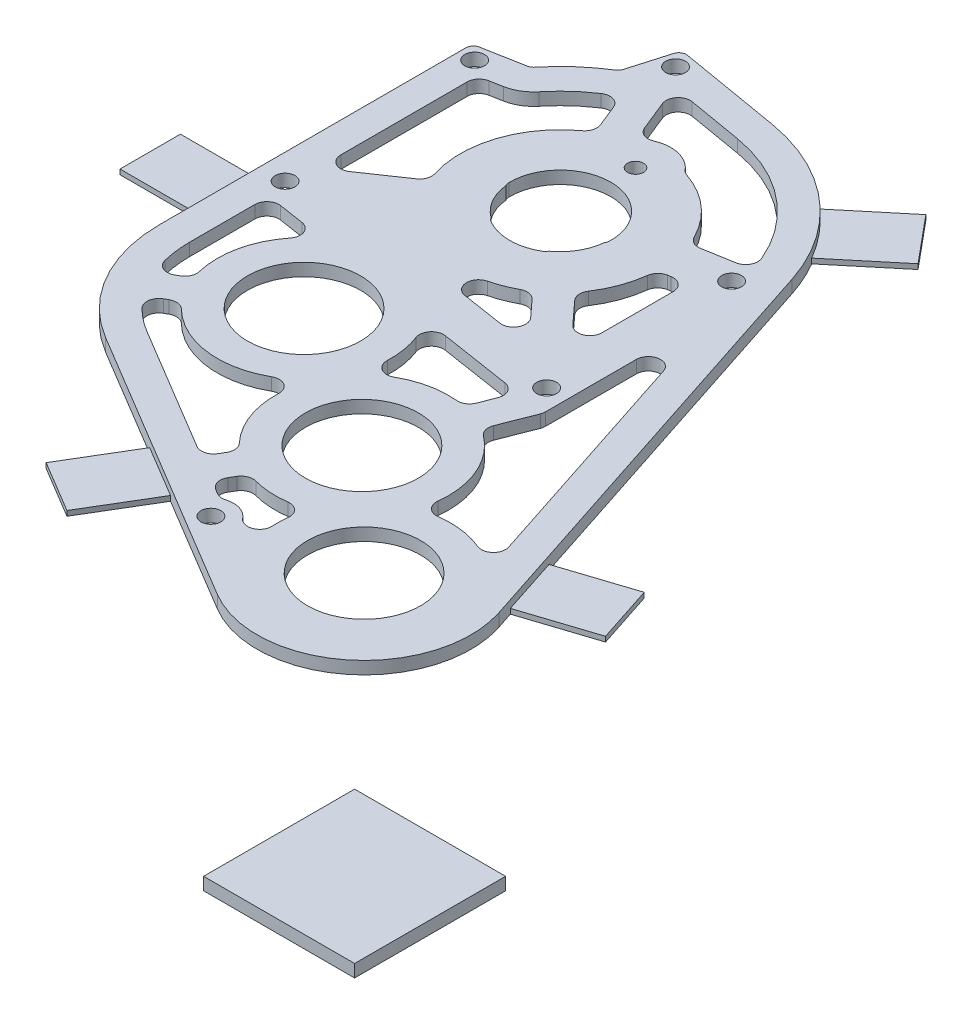
SolidWorks part; units mm, degrees
material "6061-T6 (SS)"
ref_plane "Front Plane" through (0, 0, 0) normal (0, 0, 1) x (1, 0, 0)
ref_plane "Top Plane" through (0, 0, 0) normal (0, 1, 0) x (1, 0, 0)
ref_plane "Right Plane" through (0, 0, 0) normal (1, 0, 0) x (0, 0, -1)
sketch "Underlying Sketch" plane through (0, 0, 0) normal (0, 1, 0) x (1, 0, 0)
  line L0 (316.166, 172.527) -> (324.7595, 250.8659) construction
  line L1 (305.0323, 171.3482) -> (280.2246, 246.1507) construction
  line L2 (305.0323, 171.3482) -> (280.2246, 246.1507)
  line L3 (324.7595, 250.8659) -> (316.166, 172.527)
  line L4 (352.425, 12.5969) -> (352.425, 407.9875) construction
  line L5 (352.425, 407.9875) -> (-352.425, 407.9875) construction
  line L6 (0, 407.9875) -> (0, 0) construction
  line L7 (200.025, 407.9875) -> (200.025, 255.5875) construction
  line L8 (200.025, 255.5875) -> (-200.025, 255.5875) construction
  line L9 (-200.025, 255.5875) -> (-200.025, 407.9875) construction
  line L10 (200.025, 204.7875) -> (-16.5927, 204.7875) construction
  line L11 (293.9415, 393.446) -> (335.8515, 393.446) construction
  line L12 (293.9415, 393.446) -> (293.9415, 266.446) construction
  line L13 (293.9415, 266.446) -> (335.8515, 266.446) construction
  line L14 (335.8515, 393.446) -> (335.8515, 266.446) construction
  line L15 (293.9415, 393.446) -> (335.8515, 266.446) construction
  line L16 (293.9415, 266.446) -> (335.8515, 393.446) construction
  line L17 (212.725, 407.9875) -> (212.725, 36.8617) construction
  line L18 (240.284, 194.6275) -> (324.866, 194.6275) construction
  line L19 (227.584, 181.9275) -> (227.584, 143.0655) construction
  line L20 (240.284, 130.3655) -> (324.866, 130.3655) construction
  line L21 (337.566, 181.9275) -> (337.566, 143.0655) construction
  line L22 (227.584, 143.0655) -> (212.725, 143.0655) construction
  line L23 (337.566, 143.0655) -> (352.425, 143.0655) construction
  line L24 (204.4319, 357.1875) -> (204.4319, 303.637) construction
  line L25 (240.284, 246.0625) -> (324.866, 246.0625) construction
  line L26 (227.584, 258.7625) -> (227.584, 362.6012) construction
  line L28 (337.566, 258.7625) -> (337.566, 376.6884) construction
  line L29 (314.8965, 329.946) -> (257.9415, 329.946) construction
  line L30 (257.9415, 329.946) -> (257.9415, 166.2104) construction
  line L31 (241.4315, 329.946) -> (241.4315, 166.1449) construction
  line L32 (209.55, 387.1595) -> (289.306, 387.1595) construction
  line L33 (289.306, 387.1595) -> (289.306, 273.812) construction
  line L34 (200.025, 348.1437) -> (200.025, 303.637)
  line L35 (217.8019, 272.2835) -> (310.6596, 216.7201)
  circle A0 centre (310.4706, 173.1518) radius 20.2057
  circle A1 centre (310.4706, 173.1518) radius 5.7296 construction
  circle A2 centre (301.9779, 253.365) radius 22.9183 construction
  circle A3 centre (301.9779, 253.365) radius 11.4681
  circle A7 centre (247.65, 357.1875) radius 43.2181
  circle A10 centre (236.5629, 303.637) radius 11.4681
  circle A11 centre (236.5629, 303.637) radius 32.131
  arc A12 (280.2246, 246.1507) -> (324.7595, 250.8659) centre (301.9779, 253.365) cw
  arc A13 (316.166, 172.527) -> (305.0323, 171.3482) centre (310.4706, 173.1518) cw
  circle A14 centre (273.8165, 280.9864) radius 27.9781
  circle A15 centre (273.8165, 280.9864) radius 11.4681
  circle A16 centre (247.65, 357.1875) radius 12.5 construction
  arc A19 (227.584, 143.0655) -> (240.284, 130.3655) centre (240.284, 143.0655) ccw construction
  arc A20 (324.866, 130.3655) -> (337.566, 143.0655) centre (324.866, 143.0655) ccw construction
  arc A21 (324.866, 194.6275) -> (337.566, 181.9275) centre (324.866, 181.9275) cw construction
  arc A22 (240.284, 194.6275) -> (227.584, 181.9275) centre (240.284, 181.9275) ccw construction
  circle A23 centre (247.65, 357.1875) radius 6.35 construction
  arc A24 (324.866, 246.0625) -> (337.566, 258.7625) centre (324.866, 258.7625) ccw construction
  arc A25 (240.284, 246.0625) -> (227.584, 258.7625) centre (240.284, 258.7625) cw construction
  circle A26 centre (301.9779, 253.365) radius 4.7625 construction
  circle A27 centre (273.8165, 280.9864) radius 4.7625 construction
  circle A28 centre (213.0081, 396.113) radius 8.89 construction
  circle A29 centre (213.0081, 396.113) radius 11.2395 construction
  circle A30 centre (213.0081, 396.113) radius 10.16
  circle A31 centre (273.8165, 280.9864) radius 29.21 construction
  circle A32 centre (273.8165, 280.9864) radius 10.2616 construction
  circle A33 centre (284.5435, 363.5375) radius 4.7625 construction
  arc A34 (209.55, 387.1595) -> (200.025, 348.1437) centre (247.65, 357.1875) ccw construction
  circle A35 centre (211.9378, 382.397) radius 4.7625 construction
  circle A36 centre (206.375, 329.037) radius 4.7625 construction
  circle A37 centre (284.5435, 316.865) radius 4.7625 construction
  arc A38 (200.025, 303.637) -> (217.8019, 272.2835) centre (236.5629, 303.637) ccw
  circle A39 centre (301.9779, 253.365) radius 26.9875 construction
  circle A40 centre (270.2279, 246.4633) radius 4.7625 construction
  circle A41 centre (276.098, 369.8875) radius 2.413 construction
  circle A42 centre (225.213, 369.8875) radius 2.4993 construction
  circle A43 centre (309.5625, 204.1525) radius 5.3299 construction
  circle A44 centre (284.734, 230.1875) radius 5.3299 construction
  circle A45 centre (276.098, 382.5748) radius 4.5847 construction
  circle A46 centre (250.656, 382.5748) radius 4.5847 construction
  circle A47 centre (316.5575, 253.365) radius 2.0193 construction
  circle A48 centre (287.3983, 253.365) radius 2.0193 construction
  circle A49 centre (301.9779, 253.365) radius 12.5603 construction
  point P27 (0, 407.9875)
  point P31 (0, 255.5875)
  point P44 (314.8965, 329.946)
  dimension "D1" = 11.4592
  dimension "D2" = 45.8366
  dimension "D3" = 40.4114
  dimension "D4" = 22.9362
  dimension "D5" = 86.4362
  dimension "D6" = 64.262
  dimension "D11" = 55.9562
  dimension "D7" = 25
  dimension "D24" = 12.7
  dimension "D26" = 12.7
  dimension "D29" = 9.525
  dimension "D34" = 17.78
  dimension "D35" = 22.479
  dimension "D36" = 20.32
  dimension "D37" = 58.42
  dimension "D39" = 20.5232
  dimension "D47" = 53.975
  dimension "D61" = 9.1694
  dimension "D62" = 25.1206
  dimension "D63" = 4.0386
  dimension "D64" = 9.525
  dimension "D12" = 704.85
  dimension "D15" = 400.05
  dimension "D13" = 152.4
  dimension "D16" = 47.625
  dimension "D14" = 407.9875
  dimension "D17" = 50.8
  dimension "D18" = 329.946
  dimension "D19" = 127
  dimension "D20" = 41.91
  dimension "D22" = 50.8
  dimension "D23" = 213.36
  dimension "D9" = 14.859
  dimension "D25" = 425.45
  dimension "D27" = 64.262
  dimension "D28" = 51.435
  dimension "D31" = 16.51
  dimension "D32" = 36
  dimension "D33" = 15.875
  dimension "D21" = 293.9415
  dimension "D38" = 0.635
  dimension "D30" = 2.54
  dimension "D10" = 1.27
  dimension "D40" = 20.828
  dimension "D41" = 79.756
  dimension "D42" = 4.6355
  dimension "D43" = 113.3475
  dimension "D45" = 25.4
  dimension "D46" = 63.5
  dimension "D48" = 31.75
  dimension "D50" = 38.1
  dimension "D49" = 17.8435
  dimension "D52" = 25.188
  dimension "D51" = 17.272
  dimension "D53" = 9.525
  dimension "D54" = 42.8625
  dimension "D55" = 15.875
  dimension "D56" = 52.832
  dimension "D57" = 6.35
  dimension "D58" = 6.35
  dimension "D60" = 25.442
  dimension "D59" = 50.631
sketch "Sketch2" plane through (0, 0, 0) normal (0, 1, 0) x (1, 0, 0)
  line L0 (298.0401, 171.8357) -> (322.9011, 174.4679) construction
  line L15 (328.9606, 253.8709) -> (330.4671, 173.5267)
  line L17 (352.425, 407.9875) -> (-352.425, 407.9875) construction
  line L18 (200.025, 348.1437) -> (200.025, 303.637)
  line L21 (310.4706, 173.1518) -> (301.9779, 253.365) construction
  line L22 (200.025, 407.9875) -> (200.025, 255.5875) construction
  line L25 (239.5488, 387.6675) -> (289.306, 387.6675)
  line L27 (289.306, 272.415) -> (289.306, 387.6675)
  line L28 (266.1096, 243.3776) -> (291.4873, 166.8561)
  line L29 (321.0939, 272.415) -> (289.306, 272.415)
  line L30 (305.0323, 171.3482) -> (280.2246, 246.1507) construction
  line L31 (217.8019, 272.2835) -> (266.1096, 243.3776)
  line L32 (284.226, 301.3388) -> (263.407, 260.6339) construction
  circle A0 centre (273.8165, 280.9864) radius 11.1125 construction
  circle A1 centre (236.5629, 303.637) radius 11.1125 construction
  circle A3 centre (310.4706, 173.1518) radius 12.5 construction
  circle A4 centre (322.9011, 174.4679) radius 1.7948 construction
  circle A5 centre (298.0401, 171.8357) radius 1.7948 construction
  arc A8 (330.4671, 173.5267) -> (291.4873, 166.8561) centre (310.4706, 173.1518) cw
  circle A15 centre (310.4706, 173.1518) radius 7.9375
  circle A22 centre (301.9779, 253.365) radius 11.1125 construction
  arc A35 (321.0939, 272.415) -> (328.9606, 253.8709) centre (301.9779, 253.365) cw
  circle A37 centre (285.3372, 316.865) radius 3.9688 construction
  circle A39 centre (301.9779, 253.365) radius 25.4 construction
  circle A40 centre (236.5629, 303.637) radius 33.02 construction
  circle A45 centre (270.2279, 245.5383) radius 3.9688 construction
  circle A46 centre (273.8165, 280.9864) radius 29.21 construction
  arc A47 (279.6365, 268.504) -> (321.0939, 272.415) centre (301.9779, 253.365) ccw construction
  arc A48 (200.025, 303.637) -> (217.8019, 272.2835) centre (236.5629, 303.637) ccw
  circle A49 centre (203.9938, 329.037) radius 3.9688 construction
  arc A50 (239.5488, 387.6675) -> (200.025, 348.1437) centre (239.5488, 348.1437) ccw
  circle A51 centre (247.65, 357.1875) radius 5.08
  circle A54 centre (301.9779, 253.365) radius 11.0934
  circle A55 centre (273.8165, 280.9864) radius 11.0934
  circle A56 centre (236.5629, 303.637) radius 11.0935
  point P46 (284.226, 301.3388)
  point P49 (273.8165, 280.9864)
  point P64 (263.407, 260.6339)
  dimension "D1" = 22.225
  dimension "D2" = 25
  dimension "D4" = 3.5896
  dimension "D5" = 20
  dimension "D7" = 15.875
  dimension "D8" = 26.9875
  dimension "D6" = 7.9375
  dimension "D13" = 50.8
  dimension "D14" = 66.04
  dimension "D17" = 58.42
  dimension "D11" = 10.16
  dimension "D10" = 89.281
  dimension "D3" = 20.32
  dimension "D15" = 63.5
  dimension "D18" = 31.75
  dimension "D19" = 19.05
  dimension "D9" = 25.4
  dimension "D12" = 45.72
  dimension "D16" = 5.08
  dimension "D20" = 0.019
extrude "Boss-Extrude1" [suppressed] add sketch "Sketch2" along normal blind 3.175
hole_wizard "M4 Clearance Hole1" [suppressed] positions "Sketch3" profile "Sketch4" hole size "M4" standard "ANSI Metric"
sketch "Sketch3" [suppressed] plane through (0, 3.175, 0) normal (0, 1, 0) x (1, 0, 0)
  point P0 (322.9011, 174.4679)
  point P2 (298.0401, 171.8357)
sketch "Sketch4" plane through (322.9011, 3.175, -174.4679) normal (1, 0, 0) x (0, 0, 1)
  line L0 (0, 0) -> (0, 3.175)
  line L1 (0, 3.175) -> (2.15, 3.175)
  line L2 (2.15, 3.175) -> (2.15, 0)
  line L5 (2.15, 0) -> (0, 0)
  line L11 (0, -6.35) -> (0, 107.95) construction
  dimension "Thru Hole Dia." = 4.3
  dimension "Thru Hole Depth" = 3.175
hole_wizard "CSK for #8 Flat Head Socket Cap Screw1" [suppressed] positions "Sketch5" profile "Sketch7" countersink size "#8" standard "ANSI Inch"
sketch "Sketch5" [suppressed] plane through (0, 0, 0) normal (0, -1, 0) x (-1, 0, 0)
  line L2 (-254, 357.1875) -> (-260.15, 357.1875) construction
  line L4 (-247.65, 350.8375) -> (-247.65, 344.6875) construction
  line L6 (-241.3, 357.1875) -> (-235.15, 357.1875) construction
  line L8 (-247.65, 363.5375) -> (-247.65, 369.6875) construction
  circle A0 centre (-247.65, 357.1875) radius 6.35 construction
  circle A1 centre (-247.65, 357.1875) radius 12.5 construction
  point P23 (-238.225, 357.1875)
  point P25 (-247.65, 347.7625)
  point P27 (-257.075, 357.1875)
  point P29 (-247.65, 366.6125)
sketch "Sketch7" plane through (247.65, 0, -366.6125) normal (1, 0, 0) x (0, 0, -1)
  line L0 (0, 0) -> (0, 3.175)
  line L1 (0, 3.175) -> (2.1526, 3.175)
  line L2 (2.1526, 3.175) -> (2.1526, 3.0225)
  line L3 (2.1526, 3.0225) -> (4.7801, 0)
  line L5 (4.7801, 0) -> (0, 0)
  line L6 (-2.1526, 3.0225) -> (-4.7801, 0) construction
  line L11 (0, -6.35) -> (0, 107.95) construction
  dimension "Thru Hole Dia." = 4.3053
  dimension "Thru Hole Depth" = 4.7625
  dimension "Near C'Sink Dia." = 9.5602
  dimension "Near C'Sink Angle" = 82
sketch "Sketch8" [suppressed] plane through (0, 0, 0) normal (0, -1, 0) x (1, 0, 0)
  line L0 (254.3145, -350.523) -> (247.65, -357.1875) construction
  line L1 (247.65, -357.1875) -> (260.15, -357.1875) construction
  line L2 (238.8112, -348.3487) -> (243.1599, -352.6974) construction
  circle A1 centre (247.65, -357.1875) radius 12.5 construction
  circle A2 centre (254.3145, -350.523) radius 2.1908
  circle A3 centre (254.3145, -363.852) radius 2.1908
  circle A4 centre (240.9855, -363.852) radius 2.1908
  circle A5 centre (240.9855, -350.523) radius 2.1908
  circle A6 centre (247.65, -357.1875) radius 9.425 construction
  circle A7 centre (247.65, -357.1875) radius 6.35 construction
  point P11 (240.9855, -350.523)
  point P20 (247.65, -357.1875)
  dimension "D2" = 4.3815
  dimension "D4" = 45
  dimension "D3" = 4
extrude "Cut-Extrude1" [suppressed] cut sketch "Sketch8" against normal through all
hole_wizard "#10-32 Tapped Hole1" [suppressed] positions "Sketch9" profile "Sketch10" tap size "#10-32" standard "ANSI Inch"
sketch "Sketch9" [suppressed] plane through (0, 3.175, 0) normal (0, 1, 0) x (1, 0, 0)
  point P0 (270.2279, 246.4633)
  point P3 (284.5435, 316.865)
  point P6 (284.5435, 363.5375)
  point P14 (206.375, 329.037)
  point P19 (276.098, 369.8875)
  point P23 (225.213, 369.8875)
  point P27 (309.5625, 204.1525)
  point P35 (284.734, 230.1875)
  point P41 (284.226, 301.3388)
  point P44 (263.407, 260.6339)
sketch "Sketch10" plane through (270.2279, 3.175, -246.4633) normal (1, 0, 0) x (0, 0, 1)
  line L0 (0, 0) -> (0, 3.175)
  line L1 (0, 3.175) -> (2.0193, 3.175)
  line L2 (2.0193, 3.175) -> (2.0193, 0)
  line L5 (2.0193, 0) -> (0, 0)
  line L11 (0, -6.35) -> (0, 107.95) construction
  dimension "Thru Tap Drill Dia." = 4.0386
  dimension "Thru Tap Drill Depth" = 3.175
cosmetic thread "Hole Thread3" parameters "D2"=4.826
cosmetic thread "Hole Thread5" parameters "D2"=4.826
cosmetic thread "Hole Thread6" [suppressed] parameters "D2"=4.826
cosmetic thread "Hole Thread7" [suppressed] parameters "D2"=4.826
cosmetic thread "Hole Thread9" [suppressed] parameters "D2"=4.826
cosmetic thread "Hole Thread10" [suppressed] parameters "D2"=4.826
cosmetic thread "Hole Thread11" [suppressed] parameters "D2"=4.826
cosmetic thread "Hole Thread14" [suppressed] parameters "D2"=4.826
cosmetic thread "Hole Thread16" [suppressed] parameters "D2"=4.826
cosmetic thread "Hole Thread17" [suppressed] parameters "D2"=4.826
sketch "Sketch12" plane through (0, 0, 0) normal (0, 1, 0) x (1, 0, 0)
  line L0 (200.025, 303.637) -> (200.025, 357.1875)
  line L1 (200.025, 407.9875) -> (200.025, 255.5875) construction
  line L5 (217.8019, 272.2835) -> (288.1207, 230.2068)
  line L11 (291.75, 371.5926) -> (327.6315, 261.7446)
  line L14 (200.025, 382.5838) -> (200.025, 357.1875)
  line L15 (352.425, 407.9875) -> (-352.425, 407.9875) construction
  line L16 (255.4549, 402.9194) -> (227.9505, 407.6134)
  line L17 (227.9505, 407.6134) -> (224.4061, 395.4181)
  line L19 (212.5142, 384.8882) -> (200.025, 382.5838)
  line L20 (230.6604, 403.2859) -> (247.65, 357.1875) construction
  line L21 (243.984, 382.3869) -> (240.318, 376.0372) construction
  line L22 (240.318, 376.0372) -> (243.984, 369.6875) construction
  line L23 (243.984, 369.6875) -> (251.316, 369.6875) construction
  line L24 (251.316, 369.6875) -> (254.982, 376.0372) construction
  line L25 (254.982, 376.0372) -> (251.316, 382.3869) construction
  line L26 (251.316, 382.3869) -> (243.984, 382.3869) construction
  line L27 (247.65, 357.1875) -> (203.835, 379.4125) construction
  line L28 (230.6604, 403.2859) -> (213.0081, 396.113) construction
  line L29 (213.0081, 396.113) -> (203.835, 379.4125) construction
  arc A3 (327.6315, 261.7446) -> (288.1207, 230.2068) centre (301.9779, 253.365) cw
  arc A5 (217.8019, 272.2835) -> (200.025, 303.637) centre (236.5629, 303.637) cw
  circle A8 centre (236.5629, 303.637) radius 14.2875 construction
  circle A9 centre (273.8165, 280.9864) radius 14.2875 construction
  circle A10 centre (301.9779, 253.365) radius 14.2875 construction
  circle A15 centre (213.0081, 396.113) radius 3.9687 construction
  arc A16 (255.4549, 402.9194) -> (291.75, 371.5926) centre (247.65, 357.1875) cw
  arc A18 (224.4061, 395.4181) -> (212.5142, 384.8882) centre (247.65, 357.1875) ccw
  circle A19 centre (247.65, 357.1875) radius 12.5 construction
  circle A20 centre (247.65, 376.0372) radius 5.1722 construction
  circle A21 centre (247.65, 376.1896) radius 2.0193 construction
  circle A22 centre (247.65, 357.1875) radius 43.2181 construction
  circle A23 centre (203.835, 379.4125) radius 3.81 construction
  circle A24 centre (230.6604, 403.2859) radius 3.81 construction
  circle A25 centre (273.8165, 280.9864) radius 14.2684
  circle A26 centre (301.9779, 253.365) radius 14.2684
  circle A27 centre (236.5629, 303.637) radius 14.2684
  circle A28 centre (213.0081, 396.113) radius 7.366 construction
  point P63 (247.65, 369.6875)
  dimension "D1" = 26.9875
  dimension "D3" = 28.575
  dimension "D7" = 7.9375
  dimension "D8" = 7.62
  dimension "D11" = 25
  dimension "D14" = 4.0386
  dimension "D9" = 14.732
  dimension "D12" = 7.332
  dimension "D13" = 0.1524
  dimension "D4" = 0.019
  dimension "D2" = 3.175
  dimension "D5" = 28.575
  dimension "D6" = 12.7
extrude "Boss-Extrude2" add sketch "Sketch12" along normal blind 3.175
fillet "Fillet1" [suppressed] radius 5.08
hole_wizard "#10 Clearance Hole1" positions "Sketch13" profile "Sketch14" hole size "#10" standard "ANSI Inch"
sketch "Sketch13" plane through (0, 3.175, 0) normal (0, 1, 0) x (1, 0, 0)
  point P0 (206.375, 329.037)
  point P6 (284.5435, 363.5375)
  point P9 (284.5435, 316.865)
  point P12 (270.2279, 246.4633)
  point P15 (203.835, 379.4125)
  point P18 (230.6604, 403.2859)
sketch "Sketch14" plane through (206.375, 3.175, -329.037) normal (1, 0, 0) x (0, 0, 1)
  line L0 (0, 0) -> (0, 17.3707)
  line L1 (0, 17.3707) -> (2.4892, 15.875)
  line L2 (2.4892, 15.875) -> (2.4892, 0)
  line L5 (2.4892, 0) -> (0, 0)
  line L10 (0, 17.3707) -> (-2.4892, 15.875) construction
  line L11 (0, -6.35) -> (0, 107.95) construction
  dimension "Hole Dia." = 4.9784
  dimension "Hole Depth" = 15.875
  dimension "Drill Angle" = 118
sketch "Sketch16" [suppressed] plane through (0, 0, 0) normal (0, 1, 0) x (1, 0, 0)
  line L18 (201.2282, 396.9698) -> (199.9717, 379.6935)
  line L19 (207.5383, 378.2768) -> (208.8669, 382.6093)
  line L21 (213.5243, 407.9127) -> (230.8297, 407.1557)
  line L22 (231.3586, 399.4758) -> (226.9012, 398.659)
  arc A8 (208.8669, 382.6093) -> (211.5985, 384.3864) centre (211.2953, 381.8646) cw
  arc A9 (224.8191, 396.1521) -> (226.9012, 398.659) centre (227.359, 396.1606) cw
  circle A10 centre (213.0081, 396.113) radius 5.1435
  arc A13 (211.5985, 384.3864) -> (224.8191, 396.1521) centre (213.0081, 396.113) ccw
  arc A15 (199.9717, 379.6935) -> (207.5383, 378.2768) centre (203.835, 379.4125) ccw
  arc A16 (230.8297, 407.1557) -> (231.3586, 399.4758) centre (230.6604, 403.2859) cw
  arc A17 (213.5243, 407.9127) -> (201.2282, 396.9698) centre (213.0081, 396.113) ccw
  dimension "D1" = 11.811
  dimension "D2" = 2.54
  dimension "D3" = 10.287
  dimension "D4" = 7.747
extrude "Boss-Extrude3" [suppressed] add sketch "Sketch16" along normal blind 2.286
hole_wizard "#10-32 Tapped Hole2" [suppressed] positions "Sketch17" profile "Sketch18" tap size "#10-32" standard "ANSI Inch"
sketch "Sketch17" plane through (0, 2.286, 0) normal (0, 1, 0) x (1, 0, 0)
  point P0 (203.835, 379.4125)
  point P3 (230.6604, 403.2859)
sketch "Sketch18" plane through (203.835, 2.286, -379.4125) normal (1, 0, 0) x (0, 0, 1)
  line L0 (0, 0) -> (0, 14.8277)
  line L1 (0, 14.8277) -> (2.0193, 13.6144)
  line L2 (2.0193, 13.6144) -> (2.0193, 0)
  line L5 (2.0193, 0) -> (0, 0)
  line L10 (0, 14.8277) -> (-2.0193, 13.6144) construction
  line L11 (0, -6.35) -> (0, 107.95) construction
  dimension "Tap Drill Dia." = 4.0386
  dimension "Tap Drill Depth" = 13.6144
  dimension "Drill Angle" = 118
cosmetic thread "Hole Thread12" [suppressed] parameters "D1"=2.286, "D2"=4.826
cosmetic thread "Hole Thread13" [suppressed] parameters "D1"=2.286, "D2"=4.826
hole_wizard "#10-32 Tapped Hole3 for fixture clamp" positions "Sketch19" profile "Sketch20" tap size "#10-32" standard "ANSI Inch"
sketch "Sketch19" plane through (0, 3.175, 0) normal (0, 1, 0) x (1, 0, 0)
  point P0 (247.65, 376.1896)
sketch "Sketch20" plane through (247.65, 3.175, -376.1896) normal (1, 0, 0) x (0, 0, 1)
  line L0 (0, 0) -> (0, 14.8277)
  line L1 (0, 14.8277) -> (2.0193, 13.6144)
  line L2 (2.0193, 13.6144) -> (2.0193, 0)
  line L5 (2.0193, 0) -> (0, 0)
  line L10 (0, 14.8277) -> (-2.0193, 13.6144) construction
  line L11 (0, -6.35) -> (0, 107.95) construction
  dimension "Tap Drill Dia." = 4.0386
  dimension "Tap Drill Depth" = 13.6144
  dimension "Drill Angle" = 118
cosmetic thread "Hole Thread15" parameters "D1"=3.175, "D2"=4.826
sketch "Spacer Plate" [suppressed] plane through (0, 0, 0) normal (0, 1, 0) x (1, 0, 0)
  line L5 (240.284, 194.6275) -> (324.866, 194.6275) construction
  arc A1 (293.5407, 226.5588) -> (275.2197, 230.6391) centre (284.734, 230.1875) ccw
  arc A3 (275.2197, 230.6391) -> (309.5625, 194.6275) centre (309.5625, 229.009) ccw
  arc A6 (309.5625, 194.6275) -> (306.3554, 213.1213) centre (309.5625, 204.1525) ccw
  arc A7 (306.3554, 213.1213) -> (293.5407, 226.5588) centre (302.9345, 222.6881) cw
  dimension "D1" = 9.525
  dimension "D2" = 10.16
extrude "Spacer Plate Extrude" [suppressed] add sketch "Spacer Plate" along normal blind 2.286
hole_wizard "#10 Clearance Hole2" [suppressed] positions "Sketch22" profile "Sketch23" hole size "#10" standard "ANSI Inch"
sketch "Sketch22" plane through (0, 2.286, 0) normal (0, 1, 0) x (1, 0, 0)
  point P0 (309.5625, 204.1525)
  point P3 (284.734, 230.1875)
sketch "Sketch23" plane through (309.5625, 2.286, -204.1525) normal (1, 0, 0) x (0, 0, 1)
  line L0 (0, 0) -> (0, 2.286)
  line L1 (0, 2.286) -> (2.4892, 2.286)
  line L2 (2.4892, 2.286) -> (2.4892, 0)
  line L5 (2.4892, 0) -> (0, 0)
  line L11 (0, -6.35) -> (0, 107.95) construction
  dimension "Thru Hole Dia." = 4.9784
  dimension "Thru Hole Depth" = 2.286
sketch "Sketch24" [suppressed] plane through (0, 0, 0) normal (0, 1, 0) x (1, 0, 0)
  line L1 (220.134, 387.1595) -> (246.0967, 387.1595)
  line L2 (257.5267, 376.9995) -> (220.134, 376.9995)
  line L3 (220.134, 376.9995) -> (220.134, 387.1595)
  line L4 (209.55, 387.1595) -> (289.306, 387.1595) construction
  line L11 (289.306, 387.1595) -> (289.306, 273.812) construction
  line L12 (257.5267, 376.9995) -> (257.5267, 404.495)
  line L13 (257.5267, 404.495) -> (246.0967, 404.495)
  line L14 (246.0967, 404.495) -> (246.0967, 387.1595)
  circle A0 centre (225.214, 382.0795) radius 5.08 construction
  circle A1 centre (250.656, 382.0795) radius 5.08 construction
  circle A2 centre (251.8117, 396.5575) radius 2.3813
  point P12 (251.8117, 404.495)
  dimension "D3" = 10.16
  dimension "D4" = 4.7625
  dimension "D1" = 25.442
  dimension "D2" = 38.65
  dimension "D8" = 7.9375
  dimension "D6" = 1.1557
  dimension "D5" = 14.478
  dimension "D7" = 5.715
extrude "Boss-Extrude5" [suppressed] add sketch "Sketch24" along normal blind 4.7625
hole_wizard "#10 Clearance Hole3" [suppressed] positions "Sketch26" profile "Sketch27" hole size "#10" standard "ANSI Inch"
sketch "Sketch26" plane through (0, 4.7625, 0) normal (0, 1, 0) x (1, 0, 0)
  point P0 (225.214, 382.0795)
  point P3 (250.656, 382.0795)
sketch "Sketch27" plane through (225.214, 4.7625, -382.0795) normal (1, 0, 0) x (0, 0, 1)
  line L0 (0, 0) -> (0, 4.7625)
  line L1 (0, 4.7625) -> (2.4892, 4.7625)
  line L2 (2.4892, 4.7625) -> (2.4892, 0)
  line L5 (2.4892, 0) -> (0, 0)
  line L11 (0, -6.35) -> (0, 107.95) construction
  dimension "Thru Hole Dia." = 4.9784
  dimension "Thru Hole Depth" = 4.7625
hole_wizard "#10 Clearance Hole4" [suppressed] positions "Sketch28" profile "Sketch29" hole size "#10" standard "ANSI Inch"
sketch "Sketch28" plane through (0, 3.175, 0) normal (0, 1, 0) x (1, 0, 0)
  point P0 (250.656, 382.5748)
  point P3 (276.098, 382.5748)
sketch "Sketch29" plane through (250.656, 3.175, -382.5748) normal (1, 0, 0) x (0, 0, 1)
  line L0 (0, 0) -> (0, 3.175)
  line L1 (0, 3.175) -> (2.4892, 3.175)
  line L2 (2.4892, 3.175) -> (2.4892, 0)
  line L5 (2.4892, 0) -> (0, 0)
  line L11 (0, -6.35) -> (0, 107.95) construction
  dimension "Thru Hole Dia." = 4.9784
  dimension "Thru Hole Depth" = 3.175
hole_wizard "1/4-20 Tapped Hole1" [suppressed] positions "Sketch30" profile "Sketch31" tap size "1/4-20" standard "ANSI Inch"
sketch "Sketch30" plane through (0, 2.286, 0) normal (0, 1, 0) x (1, 0, 0)
  point P0 (212.4944, 396.113)
sketch "Sketch31" plane through (212.4944, 2.286, -396.113) normal (1, 0, 0) x (0, 0, 1)
  line L0 (0, 0) -> (0, 20.5838)
  line L1 (0, 20.5838) -> (2.5527, 19.05)
  line L2 (2.5527, 19.05) -> (2.5527, 0)
  line L5 (2.5527, 0) -> (0, 0)
  line L10 (0, 20.5838) -> (-2.5527, 19.05) construction
  line L11 (0, -6.35) -> (0, 107.95) construction
  dimension "Tap Drill Dia." = 5.1054
  dimension "Tap Drill Depth" = 19.05
  dimension "Drill Angle" = 118
cosmetic thread "Hole Thread18" [suppressed] parameters "D1"=2.286, "D2"=6.35
fillet "Fillet2" radius 1.905 4 edges at (227.9505, 1.5875, -407.6134) (224.4061, 1.5875, -395.4181) (212.5142, 1.5875, -384.8882) (200.025, 1.5875, -382.5838)
fillet "Fillet3" [suppressed] radius 10.16
sketch "Sketch32" plane through (0, 3.175, 0) normal (0, 1, 0) x (1, 0, 0)
  line L0 (247.65, 376.1896) -> (247.65, 357.1875) construction
  line L1 (264.1063, 347.6865) -> (247.65, 357.1875) construction
  line L2 (231.1937, 347.6865) -> (247.65, 357.1875) construction
  line L3 (247.65, 357.1875) -> (247.65, 376.1896) construction
  line L4 (247.65, 357.1875) -> (235.219, 355.8763) construction
  line L5 (247.65, 357.1875) -> (240.299, 347.0775) construction
  line L6 (247.65, 357.1875) -> (255.001, 347.0775) construction
  line L7 (247.65, 357.1875) -> (260.081, 355.8763) construction
  arc A0 (236.6082, 350.8125) -> (254.9444, 346.7303) centre (247.65, 357.1875) ccw construction
  circle A1 centre (247.65, 357.1875) radius 12.5 construction
  arc A2 (235.219, 355.8763) -> (240.299, 347.0775) centre (247.65, 357.1875) ccw
  arc A3 (260.081, 355.8763) -> (255.001, 347.0775) centre (247.65, 357.1875) cw
  arc A4 (254.2119, 346.2557) -> (241.2323, 346.1704) centre (247.65, 357.1875) cw
  arc A5 (234.9018, 356.9706) -> (260.3982, 356.9706) centre (247.65, 357.1875) cw
  arc A6 (240.299, 347.0775) -> (240.3633, 347.0088) centre (240.1519, 346.8753) cw
  arc A7 (241.2323, 346.1704) -> (240.3633, 347.0088) centre (242.5108, 348.3652) cw
  arc A8 (235.219, 355.8763) -> (235.1849, 355.9784) centre (234.9703, 355.8501) ccw
  arc A9 (234.9018, 356.9706) -> (235.1849, 355.9784) centre (236.9016, 357.0046) ccw
  arc A10 (255.001, 347.0775) -> (254.9297, 346.997) centre (255.1481, 346.8753) ccw
  arc A11 (260.081, 355.8763) -> (260.1151, 355.9784) centre (260.3297, 355.8501) cw
  arc A12 (260.3534, 356.099) -> (234.9018, 356.9706) centre (247.65, 357.1875) ccw construction
  arc A13 (255.1481, 346.8753) -> (260.3297, 355.8501) centre (247.65, 357.1875) ccw construction
  arc A14 (254.2119, 346.2557) -> (254.9297, 346.997) centre (253.1826, 347.9705) ccw
  arc A15 (260.1151, 355.9784) -> (260.3982, 356.9706) centre (258.3984, 357.0046) ccw
  dimension "D1" = 25.5
  dimension "D3" = 10.16
  dimension "D4" = 2.54
  dimension "D5" = 0.25
  dimension "D6" = 2
  dimension "D7" = 0.25
  dimension "D8" = 0.25
  dimension "D9" = 0.25
  dimension "D10" = 2
  dimension "D2" = 3
extrude "Cut-Extrude3" cut sketch "Sketch32" against normal through all
fillet "Fillet4" [suppressed] radius 1.27
fillet "Fillet5" [suppressed] radius 25.4
sketch "Sketch33" [suppressed] plane through (0, 3.175, 0) normal (0, 1, 0) x (1, 0, 0)
  line L0 (284.5435, 363.5375) -> (247.65, 357.1875) construction
  line L1 (280.9918, 359.0602) -> (263.484, 356.0468)
  line L2 (247.65, 357.1875) -> (225.213, 369.8875) construction
  line L3 (232.3616, 361.4632) -> (227.0433, 364.4735)
  line L4 (247.65, 357.1875) -> (206.375, 329.037) construction
  line L5 (206.375, 329.037) -> (284.5435, 316.865) construction
  line L6 (284.5435, 316.865) -> (247.65, 357.1875) construction
  line L7 (248.4255, 363.8654) -> (192.898, 325.9944)
  line L8 (192.898, 325.9944) -> (298.0586, 309.6193)
  line L9 (298.0586, 309.6193) -> (248.4255, 363.8654)
  line L10 (246.8745, 350.5096) -> (219.852, 332.0796)
  line L11 (219.852, 332.0796) -> (271.0284, 324.1107)
  line L12 (271.0284, 324.1107) -> (246.8745, 350.5096)
  line L13 (236.5629, 303.637) -> (204.7784, 285.6158) construction
  line L14 (281.686, 277.495) -> (281.686, 380.0475)
  line L15 (281.686, 380.0475) -> (239.5488, 380.0475)
  line L16 (207.645, 348.1437) -> (207.645, 303.637)
  line L17 (221.7145, 278.8223) -> (261.9256, 254.7611)
  line L18 (276.3123, 236.8205) -> (298.72, 169.2548)
  line L19 (322.8484, 173.3839) -> (321.342, 253.7281)
  line L20 (317.6129, 264.795) -> (294.386, 264.795)
  line L21 (281.686, 277.495) -> (281.686, 380.0475)
  line L22 (281.686, 380.0475) -> (239.5488, 380.0475)
  line L23 (207.645, 348.1437) -> (207.645, 303.637)
  line L24 (221.7145, 278.8223) -> (261.9256, 254.7611)
  line L25 (276.3123, 236.8205) -> (298.72, 169.2548)
  line L26 (322.8484, 173.3839) -> (321.342, 253.7281)
  line L27 (317.6129, 264.795) -> (294.386, 264.795)
  line L28 (234.9969, 306.3989) -> (203.2124, 288.3777)
  line L29 (238.1289, 300.875) -> (206.3444, 282.8538)
  line L30 (309.5625, 204.1525) -> (284.734, 230.1875) construction
  line L31 (309.5625, 204.1525) -> (310.4706, 173.1518) construction
  line L32 (309.5625, 204.1525) -> (337.2541, 227.6554) construction
  line L33 (311.617, 201.7318) -> (338.0319, 224.1511)
  line L34 (306.3889, 204.0595) -> (307.297, 173.0588)
  line L35 (311.8602, 206.3437) -> (287.0317, 232.3787)
  line L36 (307.508, 206.5732) -> (333.9228, 228.9925)
  line L37 (312.7361, 204.2455) -> (313.6443, 173.2448)
  line L38 (307.2648, 201.9613) -> (282.4363, 227.9963)
  line L39 (309.5625, 204.1525) -> (335.9773, 226.5718) construction
  arc A0 (278.121, 358.5661) -> (281.686, 355.5622) centre (278.638, 355.5622) cw
  arc A1 (200.025, 303.637) -> (217.8019, 272.2835) centre (236.5629, 303.637) ccw construction
  arc A2 (281.7363, 220.4657) -> (284.6657, 224.4729) centre (284.6293, 221.4251) cw
  arc A3 (276.521, 236.1914) -> (281.2644, 234.7288) centre (279.414, 237.1508) ccw
  circle A4 centre (309.5625, 204.1525) radius 6.35
  arc A5 (290.4338, 230.6044) -> (296.5199, 235.4652) centre (295.1428, 230.9488) cw
  arc A6 (283.4952, 235.7666) -> (286.4018, 242.993) centre (282.4718, 240.376) ccw
  arc A7 (316.2412, 241.2509) -> (321.6118, 239.335) centre (318.5644, 239.2778) cw
  circle A8 centre (236.5629, 303.637) radius 18.7134
  circle A9 centre (273.8165, 280.9864) radius 18.7134
  circle A10 centre (301.9779, 253.365) radius 18.7134
  circle A11 centre (310.4706, 173.1518) radius 14.2875
  circle A12 centre (301.9779, 253.365) radius 11.0934 construction
  circle A13 centre (310.4706, 173.1518) radius 7.9375 construction
  arc A14 (247.9335, 288.7742) -> (255.3884, 284.2416) centre (250.7782, 285.056) cw
  arc A15 (254.991, 300.3817) -> (262.4459, 295.8491) centre (259.6012, 299.5674) ccw
  arc A16 (239.5488, 380.0475) -> (207.645, 348.1437) centre (239.5488, 348.1437) ccw
  arc A17 (207.645, 303.637) -> (221.7145, 278.8223) centre (236.5629, 303.637) ccw
  arc A18 (276.3123, 236.8205) -> (261.9256, 254.7611) centre (244.9709, 226.4264) ccw
  arc A19 (298.72, 169.2548) -> (322.8484, 173.3839) centre (310.4706, 173.1518) ccw
  arc A20 (321.342, 253.7281) -> (317.6129, 264.795) centre (301.9779, 253.365) ccw
  arc A21 (281.686, 277.495) -> (294.386, 264.795) centre (294.386, 277.495) ccw
  arc A22 (239.5488, 380.0475) -> (207.645, 348.1437) centre (239.5488, 348.1437) ccw
  arc A23 (207.645, 303.637) -> (221.7145, 278.8223) centre (236.5629, 303.637) ccw
  arc A24 (276.3123, 236.8205) -> (261.9256, 254.7611) centre (244.9709, 226.4264) ccw
  arc A25 (298.72, 169.2548) -> (322.8484, 173.3839) centre (310.4706, 173.1518) ccw
  arc A26 (321.342, 253.7281) -> (317.6129, 264.795) centre (301.9779, 253.365) ccw
  arc A27 (281.686, 277.495) -> (294.386, 264.795) centre (294.386, 277.495) ccw
  arc A28 (280.3878, 263.4646) -> (284.3322, 259.5959) centre (281.4581, 260.6107) cw
  circle A29 centre (263.407, 260.6339) radius 5.715
  circle A30 centre (270.2279, 246.4633) radius 5.715
  circle A31 centre (284.734, 230.1875) radius 5.715
  arc A32 (253.2897, 259.9286) -> (257.8294, 261.8797) centre (254.8547, 262.5441) ccw
  arc A33 (267.9039, 257.107) -> (270.2764, 252.1781) centre (270.3022, 255.226) ccw
  circle A34 centre (284.226, 301.3388) radius 5.715
  circle A35 centre (284.5435, 316.865) radius 5.715
  circle A36 centre (206.375, 329.037) radius 5.715
  circle A37 centre (225.213, 369.8875) radius 5.715
  circle A38 centre (276.098, 369.8875) radius 5.715
  circle A39 centre (276.098, 382.5748) radius 5.715
  circle A40 centre (250.656, 382.5748) radius 5.715
  circle A41 centre (284.5435, 363.5375) radius 5.715
  arc A42 (270.9785, 380.0475) -> (272.7592, 374.5258) centre (270.9785, 376.9995) cw
  circle A43 centre (247.65, 357.1875) radius 15.875
  arc A44 (212.4104, 339.3023) -> (207.645, 341.8204) centre (210.693, 341.8204) cw
  arc A45 (214.8214, 368.3033) -> (219.9765, 367.5982) centre (217.1838, 366.3773) cw
  arc A46 (207.645, 320.1387) -> (211.162, 323.1504) centre (210.693, 320.1387) cw
  arc A47 (281.686, 309.5586) -> (279.107, 312.5703) centre (278.638, 309.5586) ccw
  dimension "D2" = 7.62
  dimension "D3" = 6.35
  dimension "D4" = 7.62
  dimension "D5" = 3.048
  dimension "D6" = 11.43
  dimension "D7" = 31.75
  dimension "D14" = 6.35
  dimension "D15" = 12.7
  dimension "D8" = 3.81
  dimension "D9" = 3.81
  dimension "D18" = 17.78
  dimension "D1" = 7.62
  dimension "D10" = 5.08
  dimension "D11" = 5.08
  dimension "D12" = 3.175
  dimension "D13" = 3.175
  dimension "D16" = 3.175
  dimension "D17" = 3.175
extrude "Cut-Extrude4" [suppressed] cut sketch "Sketch33" against normal through all contours L24 A32 A29 A9 A14 A8 L29 A23 | A35 L8 A8 A15 A9 A34 L21 | A36 L23 A23 L28 A8 L8 | A43 L10 L11 L12 | A43 L9 L21 A0 L1 | A43 L3 A37 A22 L23 A36 L7 | A29 A33 A30 A24 L25 A3 A31 A6 A10 A28 A9 | A31 L35 A4 L36 L26 A7 A10 A5 | A31 A2 L25 A11 L34 A4 L38 | A11 L26 L33 A4 L37
fillet "Fillet6" [suppressed] radius 3.048
sketch "Sketch35" plane through (0, 3.175, 0) normal (0, 1, 0) x (1, 0, 0)
  line L0 (289.6235, 310.9327) -> (277.3646, 279.5982)
  line L1 (277.3646, 279.5982) -> (270.2684, 282.3745)
  line L2 (270.2684, 282.3745) -> (281.9109, 312.1337)
  line L3 (284.5435, 316.865) -> (247.65, 357.1875) construction
  line L4 (287.3544, 319.4369) -> (250.4609, 359.7594)
  line L5 (281.7326, 314.2931) -> (244.8391, 354.6156)
  line L6 (284.5435, 363.5375) -> (284.5435, 316.865) construction
  line L7 (284.5435, 316.865) -> (206.375, 329.037) construction
  line L8 (206.375, 329.037) -> (247.65, 357.1875) construction
  line L9 (247.65, 357.1875) -> (284.5435, 363.5375) construction
  line L10 (245.7, 362.0066) -> (289.6235, 369.5666)
  line L11 (289.6235, 369.5666) -> (289.6235, 310.9327)
  line L12 (254.1729, 395.408) -> (233.3703, 398.9583)
  line L13 (233.3703, 398.9583) -> (231.9276, 393.9942)
  line L14 (213.1993, 377.266) -> (207.645, 376.2412)
  line L15 (207.645, 376.2412) -> (207.645, 303.637)
  line L16 (221.7145, 278.8223) -> (292.0333, 236.7456)
  line L17 (320.3881, 259.3786) -> (284.5067, 369.2266)
  line L18 (254.1729, 395.408) -> (233.3703, 398.9583)
  line L19 (233.3703, 398.9583) -> (231.9276, 393.9942)
  line L20 (213.1993, 377.266) -> (207.645, 376.2412)
  line L21 (207.645, 376.2412) -> (207.645, 303.637)
  line L22 (221.7145, 278.8223) -> (292.0333, 236.7456)
  line L23 (320.3881, 259.3786) -> (284.5067, 369.2266)
  line L24 (289.6235, 310.9327) -> (192.898, 325.9944)
  line L25 (192.898, 325.9944) -> (245.7, 362.0066)
  line L26 (249.6, 352.3684) -> (279.4635, 357.5084)
  line L27 (279.4635, 357.5084) -> (279.4635, 322.7973)
  line L28 (279.4635, 322.7973) -> (219.852, 332.0796)
  line L29 (219.852, 332.0796) -> (249.6, 352.3684)
  line L30 (247.65, 357.1875) -> (226.4091, 409.6805) construction
  line L31 (251.1818, 358.6166) -> (229.9409, 411.1096)
  line L32 (244.1182, 355.7584) -> (222.8772, 408.2514)
  line L33 (273.8165, 280.9864) -> (259.1263, 256.4361) construction
  line L34 (270.5471, 282.9427) -> (255.857, 258.3924)
  line L35 (277.0859, 279.0301) -> (262.3957, 254.4798)
  line L36 (236.5629, 303.637) -> (211.4071, 289.3741) construction
  line L37 (234.6837, 306.9513) -> (209.5279, 292.6884)
  line L38 (238.4421, 300.3227) -> (213.2863, 286.0598)
  arc A0 (253.9978, 326.7626) -> (253.7312, 332.7323) centre (254.4668, 329.7743) cw
  circle A1 centre (270.2279, 246.4633) radius 5.715
  arc A2 (274.6988, 250.0231) -> (280.1261, 252.0981) centre (277.0832, 251.9217) ccw
  circle A8 centre (247.65, 357.1875) radius 25.2
  arc A10 (255.001, 347.0775) -> (260.081, 355.8763) centre (247.65, 357.1875) ccw construction
  circle A11 centre (247.65, 376.1896) radius 8.89
  circle A12 centre (236.5629, 303.637) radius 21.8884
  circle A13 centre (273.8165, 280.9864) radius 21.8884
  circle A14 centre (301.9779, 253.365) radius 21.8884
  circle A15 centre (273.8165, 280.9864) radius 14.2684 construction
  arc A16 (227.8591, 388.594) -> (231.9276, 393.9942) centre (222.781, 396.6525) ccw
  arc A17 (227.8591, 388.594) -> (218.8585, 380.6204) centre (247.65, 357.1875) ccw
  arc A18 (213.1993, 377.266) -> (218.8585, 380.6204) centre (211.471, 386.6329) ccw
  arc A19 (207.645, 303.637) -> (221.7145, 278.8223) centre (236.5629, 303.637) ccw
  arc A20 (292.0333, 236.7456) -> (320.3881, 259.3786) centre (301.9779, 253.365) ccw
  arc A21 (284.5067, 369.2266) -> (254.1729, 395.408) centre (247.65, 357.1875) ccw
  arc A22 (227.8591, 388.594) -> (231.9276, 393.9942) centre (222.781, 396.6525) ccw
  arc A23 (227.8591, 388.594) -> (218.8585, 380.6204) centre (247.65, 357.1875) ccw
  arc A24 (213.1993, 377.266) -> (218.8585, 380.6204) centre (211.471, 386.6329) ccw
  arc A25 (207.645, 303.637) -> (221.7145, 278.8223) centre (236.5629, 303.637) ccw
  arc A26 (292.0333, 236.7456) -> (320.3881, 259.3786) centre (301.9779, 253.365) ccw
  arc A27 (284.5067, 369.2266) -> (254.1729, 395.408) centre (247.65, 357.1875) ccw
  dimension "D2" = 12.7
  dimension "D5" = 17.78
  dimension "D8" = 7.62
  dimension "D14" = 3.048
  dimension "D17" = 11.43
  dimension "D13" = 7.62
  dimension "D1" = 7.62
  dimension "D3" = 5.08
  dimension "D4" = 5.08
  dimension "D6" = 3.81
  dimension "D7" = 3.81
  dimension "D9" = 3.81
  dimension "D10" = 3.81
  dimension "D11" = 3.81
  dimension "D12" = 3.81
  dimension "D15" = 3.81
  dimension "D16" = 3.81
extrude "Cut-Extrude5" cut sketch "Sketch35" against normal through all contours A24 L20 L21 L25 A8 L32 A22 A23 | L23 A27 L18 L31 A11 A8 L10 | A14 L23 L11 L0 A13 | A13 L2 L24 A12 | L38 A25 L22 L34 A13 A12 | L21 A25 L37 A12 L24 | A14 A13 L35 L22 | A8 A0 L28 L27 L26 | A8 A0 L28 L5
fillet "Fillet7" radius 3.048 38 edges at (254.3241, 1.5875, -316.4294) (223.5323, 1.5875, -321.2241) (281.9109, 1.5875, -312.1337) (278.1214, 1.5875, -302.4473) (254.1659, 1.5875, -290.6278) (256.2135, 1.5875, -293.9956) (289.6235, 1.5875, -310.9327) (289.6235, 1.5875, -353.5618) (317.2215, 1.5875, -269.0728) (294.544, 1.5875, -273.9524) (281.2504, 1.5875, -260.399) (262.3957, 1.5875, -254.4798) (266.0185, 1.5875, -260.5341) (230.0577, 1.5875, -390.5063) (234.7744, 1.5875, -378.8499) (224.3961, 1.5875, -347.4768) (207.645, 1.5875, -336.0522) (207.645, 1.5875, -376.2412) (207.645, 1.5875, -323.698) (215.9335, 1.5875, -296.3203) (209.7472, 1.5875, -292.8128) (284.6739, 1.5875, -368.7146) (271.1133, 1.5875, -366.3806) (254.9111, 1.5875, -381.3187) (241.4809, 1.5875, -382.5907) (234.9682, 1.5875, -398.6856) (219.6919, 1.5875, -289.6916) (259.4797, 1.5875, -264.4467) (255.857, 1.5875, -258.3924) (213.5056, 1.5875, -286.1841) (285.2176, 1.5875, -299.6711) (273.0358, 1.5875, -323.7981) (279.4635, 1.5875, -357.5084) (279.4635, 1.5875, -328.0613) (267.2764, 1.5875, -341.3811) (272.8367, 1.5875, -356.3679) (261.6545, 1.5875, -336.2372) (267.448, 1.5875, -251.4567)
sketch "Sketch36" plane through (0, 0, 0) normal (0, -1, 0) x (1, 0, 0)
  line L1 (386.0821, -204.9742) -> (347.9821, -204.9742)
  line L2 (386.0821, -204.9742) -> (386.0821, -166.8742)
  line L3 (386.0821, -166.8742) -> (347.9821, -166.8742)
  line L4 (347.9821, -204.9742) -> (347.9821, -166.8742)
  dimension "D1" = 38.1
extrude "Boss-Extrude6" add sketch "Sketch36" against normal through all separate body
sketch "Sketch39" plane through (0, 0, 0) normal (0, -1, 0) x (1, 0, 0)
  line L0 (200.025, -312.789) -> (200.025, -328.029)
  line L1 (200.025, -312.789) -> (180.975, -312.789)
  line L2 (200.025, -328.029) -> (180.975, -328.029)
  line L3 (180.975, -312.789) -> (180.975, -328.029)
  line L4 (200.025, -380.9982) -> (200.025, -303.637) construction
  line L5 (326.2335, -266.0243) -> (321.5015, -280.5111)
  line L6 (326.2335, -266.0243) -> (344.3419, -271.9394)
  line L7 (321.5015, -280.5111) -> (339.6099, -286.4261)
  line L8 (344.3419, -271.9394) -> (339.6099, -286.4261)
  line L9 (327.6315, -261.7446) -> (291.75, -371.5926) construction
  line L10 (258.6822, -247.8219) -> (245.6047, -255.6471)
  line L11 (258.6822, -247.8219) -> (248.9007, -231.4749)
  line L12 (245.6047, -255.6471) -> (235.8231, -239.3001)
  line L13 (248.9007, -231.4749) -> (235.8231, -239.3001)
  line L14 (217.8019, -272.2835) -> (288.1207, -230.2068) construction
  line L15 (287.7076, -380.5906) -> (277.9629, -392.308)
  line L16 (287.7076, -380.5906) -> (302.3544, -392.7715)
  line L17 (277.9629, -392.308) -> (292.6096, -404.4889)
  line L18 (302.3544, -392.7715) -> (292.6096, -404.4889)
  arc A0 (255.4549, -402.9194) -> (291.75, -371.5926) centre (247.65, -357.1875) ccw construction
  dimension "D1" = 15.24
  dimension "D2" = 19.05
extrude "Boss-Extrude8" add sketch "Sketch39" against normal blind 1.27
sketch "Sketch40" [suppressed] plane through (0, 0, 0) normal (0, -1, 0) x (1, 0, 0)
  line L1 (422.7669, -177.6457) -> (462.5058, -177.6457)
  line L2 (422.7669, -177.6457) -> (422.7669, -134.5554)
  line L3 (422.7669, -134.5554) -> (462.5058, -134.5554)
  line L4 (462.5058, -177.6457) -> (462.5058, -134.5554)
extrude "Boss-Extrude9" [suppressed] add sketch "Sketch40" against normal up to surface (3.175 mm away) separate body
sketch "Sketch41" [suppressed] plane through (0, 0, 0) normal (0, -1, 0) x (1, 0, 0)
  line L0 (286.8595, -180.8104) -> (282.0622, -195.2757)
  line L1 (286.8595, -180.8104) -> (272.3917, -176.0123)
  line L2 (282.0622, -195.2757) -> (267.5944, -190.4775)
  line L3 (272.3917, -176.0123) -> (267.5944, -190.4775)
  line L4 (269.0797, -234.4218) -> (291.4873, -166.8561) construction
  line L5 (329.8464, -206.6312) -> (329.5607, -221.8685)
  line L6 (329.8464, -206.6312) -> (345.0864, -206.9169)
  line L7 (329.5607, -221.8685) -> (344.8007, -222.1543)
  line L8 (345.0864, -206.9169) -> (344.8007, -222.1543)
  line L9 (330.4671, -173.5267) -> (328.9606, -253.8709) construction
  line L10 (289.306, -314.8013) -> (289.306, -330.0412)
  line L11 (289.306, -314.8013) -> (304.5487, -314.8013)
  line L12 (289.306, -330.0412) -> (304.5487, -330.0413)
  line L13 (304.5487, -314.8013) -> (304.5487, -330.0413)
  line L14 (289.306, -277.495) -> (289.306, -382.5875) construction
  line L15 (200.025, -322.9514) -> (201.2683, -338.1406)
  line L16 (200.025, -322.9514) -> (184.8331, -324.195)
  line L17 (201.2683, -338.1406) -> (186.0765, -339.3842)
  line L18 (184.8331, -324.195) -> (186.0765, -339.3842)
  line L19 (200.025, -348.1437) -> (200.025, -303.637) construction
  line L20 (244.8118, -256.1216) -> (231.7342, -263.9468)
  line L21 (244.8118, -256.1216) -> (236.9851, -243.0417)
  line L22 (231.7342, -263.9468) -> (223.9076, -250.8669)
  line L23 (236.9851, -243.0417) -> (223.9076, -250.8669)
  line L24 (217.8019, -272.2835) -> (258.013, -248.2223) construction
  line L25 (244.9222, -387.6675) -> (260.1622, -387.6675)
  line L26 (244.9222, -387.6675) -> (244.9222, -402.9102)
  line L27 (260.1622, -387.6675) -> (260.1622, -402.9102)
  line L28 (244.9222, -402.9102) -> (260.1622, -402.9102)
  line L29 (284.226, -387.6675) -> (239.5488, -387.6675) construction
  dimension "D1" = 15.24
  dimension "D2" = 15.24
extrude "Boss-Extrude10" [suppressed] add sketch "Sketch41" against normal blind 1.27
sketch "Sketch42" [suppressed] plane through (0, 4.7625, 0) normal (0, 1, 0) x (1, 0, 0)
  line L0 (207.5217, 411.9721) -> (215.3813, 411.9721)
  line L1 (207.5217, 411.9721) -> (207.5217, 422.3224)
  line L2 (215.3813, 411.9721) -> (215.3813, 422.3224)
  line L3 (207.5217, 422.3224) -> (215.3813, 422.3224)
extrude "Boss-Extrude12" [suppressed] add sketch "Sketch42" against normal up to surface (4.7625 mm away) separate body
sketch "Sketch44" [suppressed] plane through (0, 0, 0) normal (0, -1, 0) x (1, 0, 0)
  line L20 (226.0904, -376.9995) -> (241.3304, -376.9995)
  line L21 (226.0904, -376.9995) -> (226.0904, -361.7595)
  line L22 (241.3304, -376.9995) -> (241.3304, -361.7595)
  line L23 (226.0904, -361.7595) -> (241.3304, -361.7595)
  line L24 (221.404, -376.9995) -> (256.2567, -376.9995) construction
  line L25 (257.5267, -382.4732) -> (257.5267, -397.7132)
  line L26 (257.5267, -382.4732) -> (272.7667, -382.4732)
  line L27 (257.5267, -397.7132) -> (272.7667, -397.7132)
  line L28 (272.7667, -382.4732) -> (272.7667, -397.7132)
  line L29 (257.5267, -378.2695) -> (257.5267, -403.225) construction
  dimension "D1" = 15.24
  dimension "D2" = 15.24
extrude "Boss-Extrude13" [suppressed] add sketch "Sketch44" against normal blind 1.27
sketch "Sketch45" [suppressed] plane through (0, 0, 0) normal (0, -1, 0) x (1, 0, 0)
  line L9 (154.6683, -344.3741) -> (187.7433, -344.3741)
  line L10 (154.6683, -344.3741) -> (154.6683, -371.8113)
  line L11 (154.6683, -371.8113) -> (187.7433, -371.8113)
  line L12 (187.7433, -344.3741) -> (187.7433, -371.8113)
extrude "Boss-Extrude14" [suppressed] add sketch "Sketch45" against normal up to surface (2.286 mm away) separate body contours L9 L12 L11 L10
sketch "Sketch46" [suppressed] plane through (0, 2.286, 0) normal (0, 1, 0) x (1, 0, 0)
  line L0 (203.8085, 391.4684) -> (201.5009, 378.9798)
  line L1 (203.8085, 391.4684) -> (179.3642, 395.9852)
  line L2 (201.5009, 378.9798) -> (177.0565, 383.4966)
  line L3 (179.3642, 395.9852) -> (177.0565, 383.4966)
  line L10 (223.3514, 401.8153) -> (210.7007, 402.9339)
  line L11 (223.3514, 401.8153) -> (225.5408, 426.5768)
  line L12 (210.7007, 402.9339) -> (212.8901, 427.6954)
  line L13 (225.5408, 426.5768) -> (212.8901, 427.6954)
  arc A0 (211.5985, 384.3864) -> (224.8191, 396.1521) centre (213.0081, 396.113) ccw construction
  dimension "D1" = 12.7
extrude "Boss-Extrude15" [suppressed] add sketch "Sketch46" against normal blind 1.27
sketch "Sketch47" [suppressed] plane through (0, 0, 0) normal (0, -1, 0) x (1, 0, 0)
  line L1 (229.7393, -185.5228) -> (250.452, -185.5228)
  line L2 (229.7393, -185.5228) -> (229.7393, -206.2354)
  line L3 (229.7393, -206.2354) -> (250.452, -206.2354)
  line L4 (250.452, -185.5228) -> (250.452, -206.2354)
extrude "Boss-Extrude16" [suppressed] add sketch "Sketch47" against normal up to surface (2.286 mm away) separate body
sketch "Sketch48" [suppressed] plane through (0, 2.286, 0) normal (0, 1, 0) x (1, 0, 0)
  line L0 (306.4367, 196.4014) -> (293.8956, 198.4045)
  line L1 (306.4367, 196.4014) -> (304.3996, 183.6479)
  line L2 (293.8956, 198.4045) -> (291.8586, 185.651)
  line L3 (304.3996, 183.6479) -> (291.8586, 185.651)
  line L4 (291.0212, 237.3427) -> (280.9884, 238.9451)
  line L5 (291.0212, 237.3427) -> (293.0583, 250.0962)
  line L6 (280.9884, 238.9451) -> (283.0254, 251.6986)
  line L7 (293.0583, 250.0962) -> (283.0254, 251.6986)
  arc A0 (275.2197, 230.6391) -> (309.5625, 194.6275) centre (309.5625, 229.009) ccw construction
  arc A1 (293.5407, 226.5588) -> (275.2197, 230.6391) centre (284.734, 230.1875) ccw construction
  dimension "D1" = 12.7
  dimension "D2" = 10.16
extrude "Boss-Extrude17" [suppressed] add sketch "Sketch48" against normal blind 1.27
equation "\"D1@Underlying Sketch\" = 3mm * 12 / pi"
equation "\"D2@Underlying Sketch\" = 3mm * 48 / pi"
equation "\"D4@Underlying Sketch\" = 18 / 20 + 0.003"
equation "\"D5@Underlying Sketch\"=68 / 20 + 0.003"
equation "\"D6@Underlying Sketch\" = 50 / 20 + 0.03"
equation "\"D2@Sketch2\"=25mm"
equation "\"D11@Underlying Sketch\" = 44 / 20 + 0.003"
equation "\"D14@Underlying Sketch\" = 32.125in / 2"
equation "\"D34@Underlying Sketch\" = 14 / 20"
equation "\"D12@Sketch12\"=7.332mm"
equation "\"D2@Sketch24\"=38.650mm"
equation "\"D60@Underlying Sketch\"=25.442mm"
equation "\"D59@Underlying Sketch\"=50.631mm"
equation "\"D62@Underlying Sketch\"=.969+.02"
